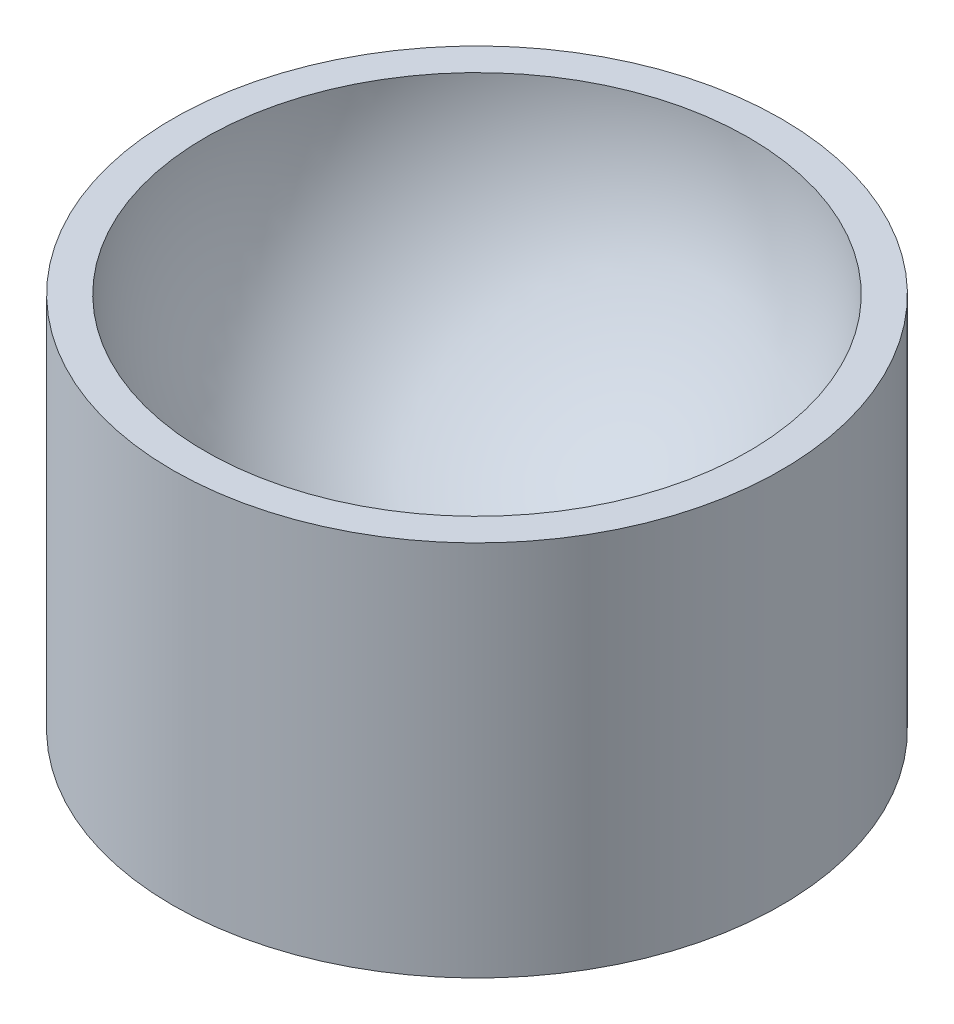
SolidWorks part; units mm, degrees
ref_plane "Front Plane" through (0, 0, 0) normal (0, 0, 1) x (1, 0, 0)
ref_plane "Top Plane" through (0, 0, 0) normal (0, 1, 0) x (1, 0, 0)
ref_plane "Right Plane" through (0, 0, 0) normal (1, 0, 0) x (0, 0, -1)
sketch "Sketch2" plane through (0, 0, 0) normal (0, 1, 0) x (1, 0, 0)
  line L1 (0, 7.5056) -> (-6.5, 3.7528)
  line L2 (-6.5, 3.7528) -> (-6.5, -3.7528)
  line L3 (-6.5, -3.7528) -> (0, -7.5056)
  line L4 (0, -7.5056) -> (6.5, -3.7528)
  line L5 (6.5, -3.7528) -> (6.5, 3.7528)
  line L6 (6.5, 3.7528) -> (0, 7.5056)
  circle A0 centre (0, 0) radius 42
  circle A1 centre (0, 0) radius 6.5 construction
  dimension "D1" = 84
  dimension "D2" = 13
extrude "Boss-Extrude1" add sketch "Sketch2" along normal blind 11.5
sketch "Sketch3" plane through (0, 0, 0) normal (0, -1, 0) x (1, 0, 0)
  circle A0 centre (0, 0) radius 8
  dimension "D1" = 16
extrude "Cut-Extrude1" cut sketch "Sketch3" against normal blind 7
sketch "Sketch4" plane through (0, 0, 0) normal (0, 0, 1) x (1, 0, 0)
  line L0 (0, 0) -> (0, 52) construction
  line L1 (4.05, 14.7193) -> (4.05, 11.5)
  line L2 (4.05, 11.5) -> (42, 11.5)
  line L4 (42, 11.5) -> (-42, 11.5) construction
  line L5 (42, 11.5) -> (42, 52)
  line L6 (42, 52) -> (37.5, 52)
  arc A0 (4.05, 14.7193) -> (37.5, 52) centre (0, 52) ccw
  dimension "D1" = 75
  dimension "D2" = 3
  dimension "D3" = 4.05
revolve "Revolve1" add sketch "Sketch4" angle 360 about L0
